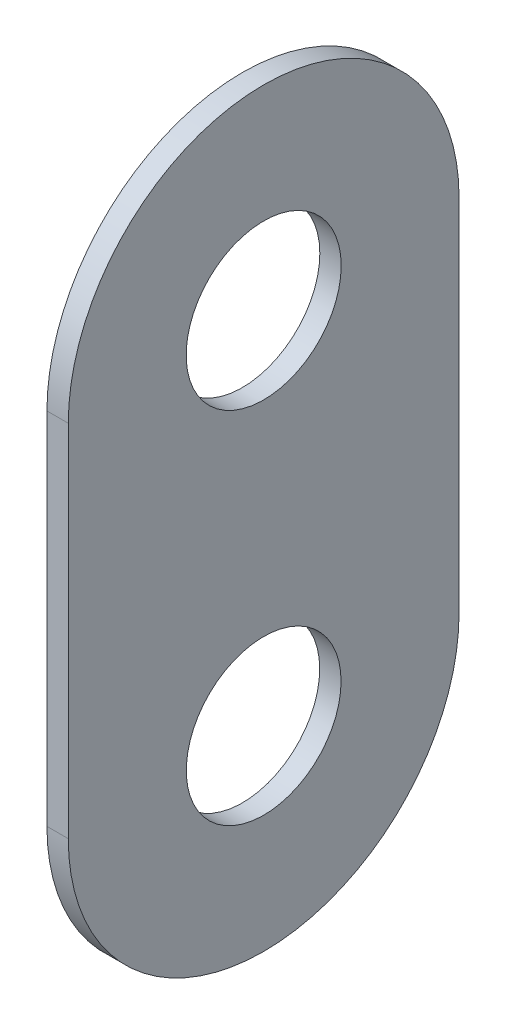
SolidWorks part; units mm, degrees
ref_plane "Front Plane" through (0, 0, 0) normal (0, 0, 1) x (1, 0, 0)
ref_plane "Top Plane" through (0, 0, 0) normal (0, 1, 0) x (1, 0, 0)
ref_plane "Right Plane" through (0, 0, 0) normal (1, 0, 0) x (0, 0, -1)
sketch "Sketch1" plane through (0, 0, 0) normal (1, 0, 0) x (0, 0, -1)
  line L0 (0, 82.3691) -> (0, -86.1132) construction
  line L1 (91.5, 82.3691) -> (91.5, -86.1131)
  line L2 (-91.5, 82.3691) -> (-91.5, -86.1132)
  arc A0 (91.5, 82.3691) -> (-91.5, 82.3691) centre (0, 82.3691) ccw
  arc A1 (-91.5, -86.1132) -> (91.5, -86.1131) centre (0, -86.1132) ccw
  circle A2 centre (0, 82.3691) radius 36.3
  circle A3 centre (0, -86.1132) radius 36.2419
  point P3 (0, -1.872)
  dimension "D2" = 91.5
  dimension "D3" = 72.6
  dimension "D4" = 72.4838
  dimension "D1" = 168.4822
extrude "Boss-Extrude1" add sketch "Sketch1" along normal blind 10
